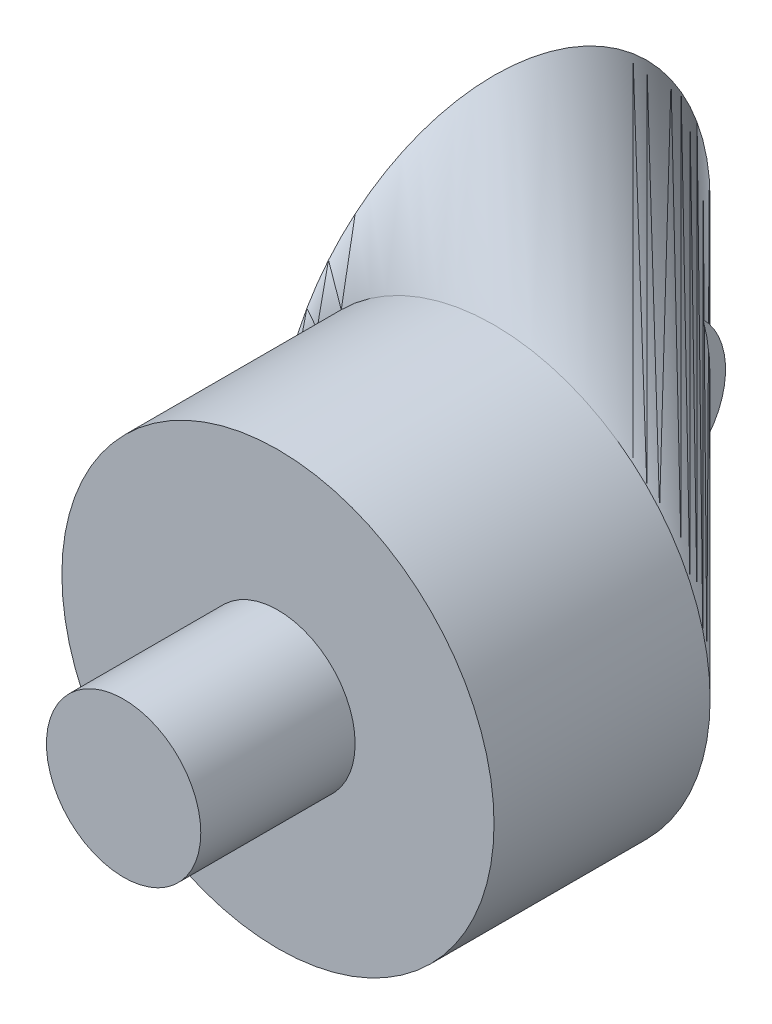
SolidWorks part; units mm, degrees
ref_plane "Front Plane" through (0, 0, 0) normal (0, 0, 1) x (1, 0, 0)
ref_plane "Top Plane" through (0, 0, 0) normal (0, 1, 0) x (1, 0, 0)
ref_plane "Right Plane" through (0, 0, 0) normal (1, 0, 0) x (0, 0, -1)
sketch "Sketch1" plane through (0, 0, 0) normal (1, 0, 0) x (0, 0, -1)
  circle A0 centre (0, 0) radius 70
  dimension "D1" = 140
sketch "Sketch2" plane through (0, 0, 0) normal (0, 1, 0) x (1, 0, 0)
  line L1 (0, -70) -> (0, 70) construction
  line L2 (0, -77) -> (0, 77) construction
  arc A0 (70, -70) -> (0, 0) centre (0, -70) ccw
sweep "Sweep1" add profiles "Sketch1" path "Sketch2"
sketch "Sketch4" plane through (0, 0, 0) normal (-1, 0, 0) x (0, 0, 1)
  circle A0 centre (0, 0) radius 25
extrude "Cut-Extrude1" cut sketch "Sketch4" against normal blind 50
sketch "Sketch5" plane through (0, 0, 70) normal (0, 0, 1) x (1, 0, 0)
  line L0 (70, 0) -> (0, 0) construction
  line L1 (77, 0) -> (-77, 0) construction
  circle A0 centre (70, 0) radius 70
extrude "Boss-Extrude2" add sketch "Sketch5" along normal blind 70
sketch "Sketch6" plane through (0, 0, 140) normal (0, 0, 1) x (1, 0, 0)
  line L0 (70, 0) -> (0, 0) construction
  circle A0 centre (70, 0) radius 25
extrude "Boss-Extrude3" add sketch "Sketch6" along normal blind 50
